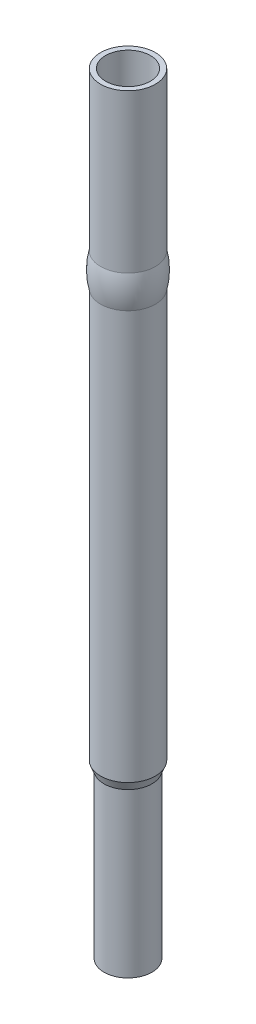
SolidWorks part; units mm, degrees
material "Nickel silver 65-12, UNS C75700"
ref_plane "Front" through (0, 0, 0) normal (0, 0, 1) x (1, 0, 0)
ref_plane "Top" through (0, 0, 0) normal (0, 1, 0) x (1, 0, 0)
ref_plane "Right" through (0, 0, 0) normal (1, 0, 0) x (0, 0, -1)
sketch "Sketch1" plane through (0, 0, 0) normal (1, 0, 0) x (0, 0, -1)
  line L0 (0.685, 0) -> (0.685, -14.48)
  line L1 (0.685, -14.48) -> (0, -14.48)
  line L2 (0, -14.48) -> (0, -18.62)
  line L3 (0, -18.62) -> (0.595, -18.62)
  line L4 (0.595, -18.62) -> (0.595, -23.62)
  line L5 (0.595, -23.62) -> (0.735, -23.62)
  line L6 (0.735, -23.62) -> (0.735, -18.62)
  line L7 (0.735, -18.62) -> (0.84, -18.36)
  line L8 (0.84, -18.36) -> (0.84, -5.84)
  line L9 (0.84, -5.84) -> (0.84, -4.84) construction
  line L10 (0.84, -4.84) -> (0.84, 0)
  line L11 (0.84, 0) -> (0.685, 0)
  arc A0 (0.84, -4.84) -> (0.84, -5.84) centre (-1.2133, -5.34) cw
  point P9 (0.7875, -18.49)
  point P11 (0.9, -5.34)
  dimension "D1" = 0.595
  dimension "D2" = 0.735
  dimension "D3" = 0.84
  dimension "D4" = 0.685
  dimension "D5" = 23.62
  dimension "D6" = 18.49
  dimension "D7" = 0.9
  dimension "D8" = 5.84
  dimension "D9" = 14.48
  dimension "D10" = 5
  dimension "D11" = 1
revolve "Revolve1" add sketch "Sketch1" angle 360 about L2
equation "\"D9@Sketch1\"=24.64-6.1-4.06"
